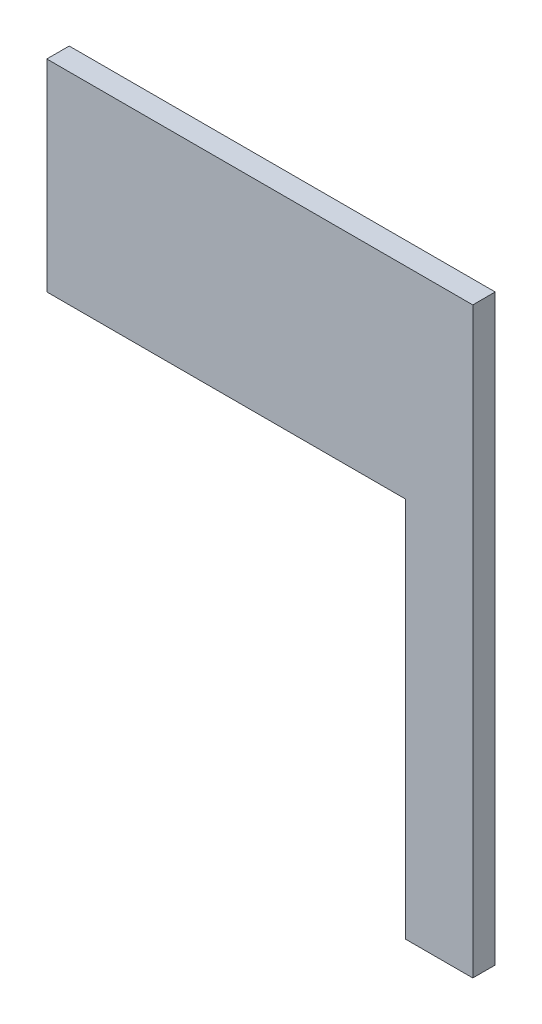
SolidWorks part; units mm, degrees
material "6061-T6 (SS)"
ref_plane "Front Plane" through (0, 0, 0) normal (0, 0, 1) x (1, 0, 0)
ref_plane "Top Plane" through (0, 0, 0) normal (0, 1, 0) x (1, 0, 0)
ref_plane "Right Plane" through (0, 0, 0) normal (1, 0, 0) x (0, 0, -1)
sketch "Sketch1" plane through (0, 0, 0) normal (0, 0, 1) x (1, 0, 0)
  line L0 (0, 0) -> (80, 0)
  line L1 (0, 0) -> (0, 45)
  line L5 (0, 45) -> (85, 45)
  line L6 (80, 0) -> (80, -85)
  line L7 (85, 45) -> (95, 45)
  line L8 (95, 45) -> (95, -85)
  line L9 (95, -85) -> (80, -85)
extrude "Boss-Extrude1" add sketch "Sketch1" along normal blind 5
